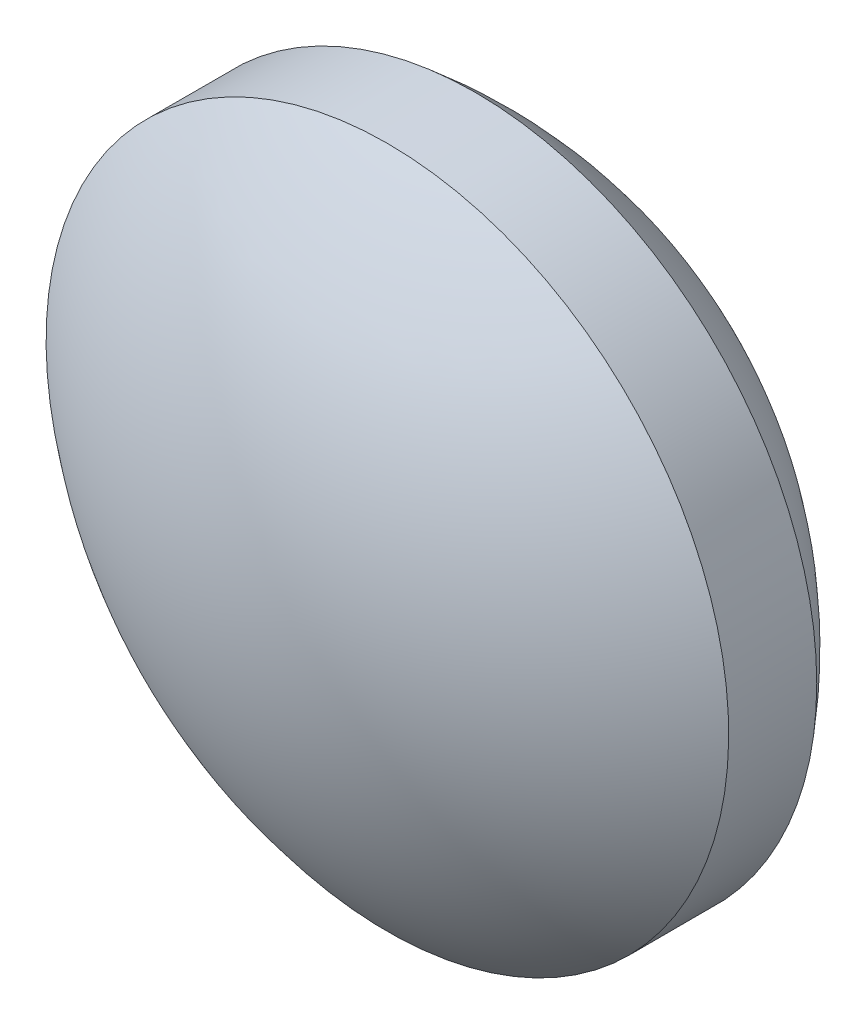
SolidWorks part; units mm, degrees
ref_plane "Front Plane" through (0, 0, 0) normal (0, 0, 1) x (1, 0, 0)
ref_plane "Top Plane" through (0, 0, 0) normal (0, 1, 0) x (1, 0, 0)
ref_plane "Right Plane" through (0, 0, 0) normal (1, 0, 0) x (0, 0, -1)
sketch "Sketch3" plane through (0, 0, 0) normal (1, 0, 0) x (0, 0, -1)
  line L1 (0, 0) -> (0, 3.875)
  line L2 (-0.5, 3.875) -> (0.5, 3.875)
  line L3 (0, 0) -> (-2.6598, 0)
  line L4 (0, 0) -> (4.0809, 0)
  arc A0 (2.3402, 0) -> (0.5, 3.875) centre (-2.6598, 0) ccw
  arc A2 (-0.5, 3.875) -> (-1.9191, 0) centre (4.0809, 0) ccw
  dimension "D1" = 2.3402
  dimension "D2" = 3.875
  dimension "D3" = 0.5
  dimension "D4" = 2.6598
  dimension "D5" = 4.0809
revolve "Revolve1" add sketch "Sketch3" angle 360 about L3
equation "\"T_edge\"= \"gloabl_scale\" * 1mm"
equation "\"R_right\"= \"gloabl_scale\" * 5mm"
equation "\"dT_c_right\"= \"R_right\" * ( 1 - sqr ( 1 - \"h\" ^ 2 / \"R_right\" ^ 2 ) )"
equation "\"h\"= \"gloabl_scale\" * 7.75 / 2mm"
equation "\"gloabl_scale\"= 1"
equation "\"x_sphere_origin_right\"= \"R_right\" - \"dT_c_right\" - \"T_edge\" / 2"
equation "\"half_T_c_right\" = \"T_edge\" / 2 + \"dT_c_right\""
equation "\"D1@Sketch3\" = \"half_T_c_right\""
equation "\"D2@Sketch3\"=\"h\""
equation "\"D3@Sketch3\"=\"T_edge\" / 2"
equation "\"D4@Sketch3\"=\"x_sphere_origin_right\""
equation "\"R_left\"= \"gloabl_scale\" * 6mm"
equation "\"dT_c_left\"= \"R_left\" * ( 1 - sqr ( 1 - \"h\" ^ 2 / \"R_left\" ^ 2 ) )"
equation "\"half_T_c_left\"= \"T_edge\" / 2 + \"dT_c_left\""
equation "\"x_sphere_origin_left\" = \"R_left\" - \"dT_c_left\" - \"T_edge\" / 2"
equation "\"D5@Sketch3\"=\"x_sphere_origin_left\""
